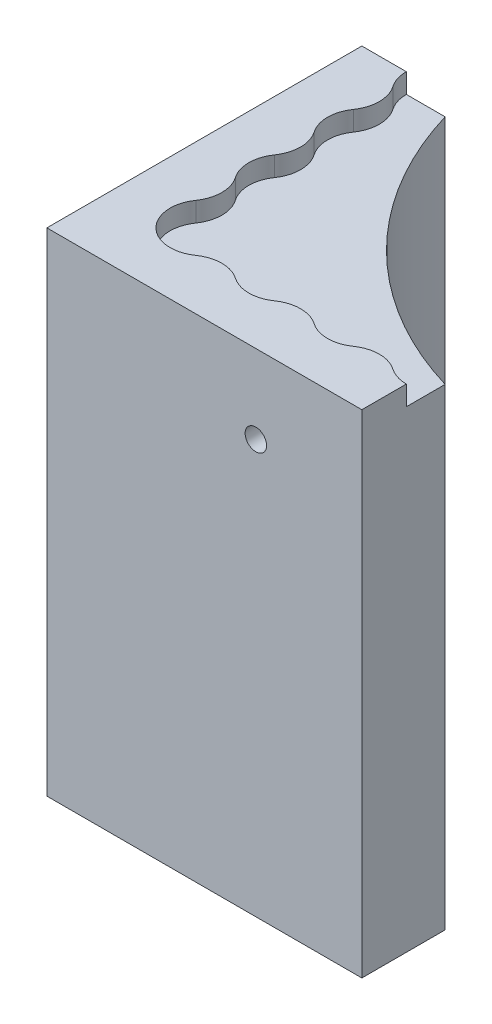
SolidWorks part; units mm, degrees
material "PET"
ref_plane "Front" through (0, 0, 0) normal (0, 0, 1) x (1, 0, 0)
ref_plane "Top" through (0, 0, 0) normal (0, 1, 0) x (1, 0, 0)
ref_plane "Right" through (0, 0, 0) normal (1, 0, 0) x (0, 0, -1)
sketch "Sketch1" plane through (0, 0, 0) normal (0, 1, 0) x (1, 0, 0)
  line L1 (0, 0) -> (50.8, 0)
  line L2 (0, 0) -> (0, 50.8)
  line L3 (0, 50.8) -> (50.8, 50.8)
  line L4 (50.8, 0) -> (50.8, 50.8)
  circle A0 centre (66.675, 66.675) radius 55.5625 construction
  dimension "D1" = 66.675
  dimension "D2" = 111.125
  dimension "D3" = 66.675
  dimension "D4" = 50.8
extrude "Boss-Extrude1" add sketch "Sketch1" along normal blind 79.375
sketch "Sketch2" plane through (0, 79.375, 0) normal (0, 1, 0) x (1, 0, 0)
  line L8 (129.2582, 124.9484) -> (133.499, 78.5045) construction
  line L9 (85.192, 137.4546) -> (125.4736, 129.1805) construction
  line L10 (129.2582, 124.9484) -> (133.499, 78.5045) construction
  line L11 (85.192, 137.4546) -> (125.4736, 129.1805) construction
  line L12 (130.017, 125.0177) -> (134.2578, 78.5738)
  line L13 (85.3453, 138.201) -> (125.6269, 129.9269)
  arc A0 (8.7916, 91.6214) -> (8.7916, 98.8786) centre (3.5805, 95.25) ccw construction
  arc A1 (8.7916, 91.6214) -> (8.7916, 86.1786) centre (12.7, 88.9) ccw construction
  arc A2 (8.7916, 78.9214) -> (8.7916, 86.1786) centre (3.5805, 82.55) ccw construction
  arc A3 (8.7916, 78.9214) -> (8.7796, 73.4959) centre (12.7, 76.2) ccw construction
  arc A4 (8.8014, 66.3169) -> (8.7796, 73.4959) centre (3.5524, 69.8905) ccw construction
  arc A5 (8.8014, 66.3169) -> (8.8053, 60.7032) centre (12.9199, 63.5129) ccw construction
  arc A6 (8.7834, 53.5096) -> (8.8053, 60.7032) centre (3.5613, 57.1223) ccw construction
  arc A7 (8.7834, 53.5096) -> (8.7916, 48.0786) centre (12.7, 50.8) ccw construction
  arc A8 (8.7916, 40.8214) -> (8.7916, 48.0786) centre (3.5805, 44.45) ccw construction
  arc A9 (8.7916, 40.8214) -> (8.7916, 35.3786) centre (12.7, 38.1) ccw construction
  arc A10 (8.7916, 28.1214) -> (8.7916, 35.3786) centre (3.5805, 31.75) ccw construction
  arc A11 (8.7916, 28.1214) -> (8.7916, 22.6786) centre (12.7, 25.4) ccw construction
  arc A12 (8.7916, 15.4214) -> (8.7916, 22.6786) centre (3.5805, 19.05) ccw construction
  arc A13 (8.7916, 15.4214) -> (15.4214, 8.7916) centre (12.7, 12.7) ccw construction
  arc A14 (22.6786, 8.7916) -> (15.4214, 8.7916) centre (19.05, 3.5805) ccw construction
  arc A15 (22.6786, 8.7916) -> (28.1214, 8.7916) centre (25.4, 12.7) ccw construction
  arc A16 (35.3786, 8.7916) -> (28.1214, 8.7916) centre (31.75, 3.5805) ccw construction
  arc A17 (35.3786, 8.7916) -> (40.8214, 8.7916) centre (38.1, 12.7) ccw construction
  arc A18 (48.0786, 8.7916) -> (40.8214, 8.7916) centre (44.45, 3.5805) ccw construction
  arc A19 (48.0786, 8.7916) -> (53.5096, 8.7834) centre (50.8, 12.7) ccw construction
  arc A20 (60.7032, 8.8053) -> (53.5096, 8.7834) centre (57.1223, 3.5613) ccw construction
  arc A21 (60.7032, 8.8053) -> (66.3169, 8.8014) centre (63.5129, 12.9199) ccw construction
  arc A22 (73.4959, 8.7796) -> (66.3169, 8.8014) centre (69.8905, 3.5524) ccw construction
  arc A23 (73.4959, 8.7796) -> (78.9214, 8.7916) centre (76.2, 12.7) ccw construction
  arc A24 (86.1786, 8.7916) -> (78.9214, 8.7916) centre (82.55, 3.5805) ccw construction
  arc A25 (86.1786, 8.7916) -> (91.6214, 8.7916) centre (88.9, 12.7) ccw construction
  arc A26 (98.8786, 8.7916) -> (91.6214, 8.7916) centre (95.25, 3.5805) ccw construction
  arc A27 (98.8786, 8.7916) -> (105.5642, 15.3394) centre (101.6, 12.7) ccw construction
  arc A28 (113.5841, 27.9306) -> (105.5642, 15.3394) centre (112.3572, 19.8624) ccw construction
  arc A29 (113.5841, 27.9306) -> (119.0625, 32.6538) centre (114.3, 32.639) ccw construction
  arc A30 (119.9168, 35.8549) -> (119.0625, 32.6538) centre (125.4124, 32.6736) ccw construction
  arc A31 (119.9168, 35.8549) -> (127.8227, 59.9277) centre (66.675, 66.675) ccw construction
  arc A32 (132.1466, 72.652) -> (127.8227, 59.9277) centre (158.75, 56.515) ccw construction
  arc A33 (132.1466, 72.652) -> (133.499, 78.5045) centre (123.9376, 77.6314) ccw construction
  arc A34 (129.2582, 124.9484) -> (125.4736, 129.1805) centre (124.5154, 124.5154) ccw construction
  arc A35 (85.192, 137.4546) -> (76.9535, 135.2891) centre (83.2602, 128.0498) ccw construction
  arc A36 (59.9277, 127.8227) -> (76.9535, 135.2891) centre (56.515, 158.75) ccw construction
  arc A37 (59.9277, 127.8227) -> (35.8549, 119.9168) centre (66.675, 66.675) ccw construction
  arc A38 (32.6538, 119.0625) -> (35.8549, 119.9168) centre (32.6736, 125.4124) ccw construction
  arc A39 (32.6538, 119.0625) -> (27.9306, 113.5841) centre (32.639, 114.3) ccw construction
  arc A40 (15.3394, 105.5642) -> (27.9306, 113.5841) centre (19.8624, 112.3572) ccw construction
  arc A41 (15.3394, 105.5642) -> (8.7916, 98.8786) centre (12.7, 101.6) ccw construction
  arc A42 (8.7916, 91.6214) -> (8.7916, 98.8786) centre (3.5805, 95.25) ccw construction
  arc A43 (8.7916, 91.6214) -> (8.7916, 86.1786) centre (12.7, 88.9) ccw construction
  arc A44 (8.7916, 78.9214) -> (8.7916, 86.1786) centre (3.5805, 82.55) ccw construction
  arc A45 (8.7916, 78.9214) -> (8.7796, 73.4959) centre (12.7, 76.2) ccw construction
  arc A46 (8.8014, 66.3169) -> (8.7796, 73.4959) centre (3.5524, 69.8905) ccw construction
  arc A47 (8.8014, 66.3169) -> (8.8053, 60.7032) centre (12.9199, 63.5129) ccw construction
  arc A48 (8.7834, 53.5096) -> (8.8053, 60.7032) centre (3.5613, 57.1223) ccw construction
  arc A49 (8.7834, 53.5096) -> (8.7916, 48.0786) centre (12.7, 50.8) ccw construction
  arc A50 (8.7916, 40.8214) -> (8.7916, 48.0786) centre (3.5805, 44.45) ccw construction
  arc A51 (8.7916, 40.8214) -> (8.7916, 35.3786) centre (12.7, 38.1) ccw construction
  arc A52 (8.7916, 28.1214) -> (8.7916, 35.3786) centre (3.5805, 31.75) ccw construction
  arc A53 (8.7916, 28.1214) -> (8.7916, 22.6786) centre (12.7, 25.4) ccw construction
  arc A54 (8.7916, 15.4214) -> (8.7916, 22.6786) centre (3.5805, 19.05) ccw construction
  arc A55 (8.7916, 15.4214) -> (15.4214, 8.7916) centre (12.7, 12.7) ccw construction
  arc A56 (22.6786, 8.7916) -> (15.4214, 8.7916) centre (19.05, 3.5805) ccw construction
  arc A57 (22.6786, 8.7916) -> (28.1214, 8.7916) centre (25.4, 12.7) ccw construction
  arc A58 (35.3786, 8.7916) -> (28.1214, 8.7916) centre (31.75, 3.5805) ccw construction
  arc A59 (35.3786, 8.7916) -> (40.8214, 8.7916) centre (38.1, 12.7) ccw construction
  arc A60 (48.0786, 8.7916) -> (40.8214, 8.7916) centre (44.45, 3.5805) ccw construction
  arc A61 (48.0786, 8.7916) -> (53.5096, 8.7834) centre (50.8, 12.7) ccw construction
  arc A62 (60.7032, 8.8053) -> (53.5096, 8.7834) centre (57.1223, 3.5613) ccw construction
  arc A63 (60.7032, 8.8053) -> (66.3169, 8.8014) centre (63.5129, 12.9199) ccw construction
  arc A64 (73.4959, 8.7796) -> (66.3169, 8.8014) centre (69.8905, 3.5524) ccw construction
  arc A65 (73.4959, 8.7796) -> (78.9214, 8.7916) centre (76.2, 12.7) ccw construction
  arc A66 (86.1786, 8.7916) -> (78.9214, 8.7916) centre (82.55, 3.5805) ccw construction
  arc A67 (86.1786, 8.7916) -> (91.6214, 8.7916) centre (88.9, 12.7) ccw construction
  arc A68 (98.8786, 8.7916) -> (91.6214, 8.7916) centre (95.25, 3.5805) ccw construction
  arc A69 (98.8786, 8.7916) -> (105.5642, 15.3394) centre (101.6, 12.7) ccw construction
  arc A70 (113.5841, 27.9306) -> (105.5642, 15.3394) centre (112.3572, 19.8624) ccw construction
  arc A71 (113.5841, 27.9306) -> (119.0625, 32.6538) centre (114.3, 32.639) ccw construction
  arc A72 (119.9168, 35.8549) -> (119.0625, 32.6538) centre (125.4124, 32.6736) ccw construction
  arc A73 (119.9168, 35.8549) -> (127.8227, 59.9277) centre (66.675, 66.675) ccw construction
  arc A74 (132.1466, 72.652) -> (127.8227, 59.9277) centre (158.75, 56.515) ccw construction
  arc A75 (132.1466, 72.652) -> (133.499, 78.5045) centre (123.9376, 77.6314) ccw construction
  arc A76 (129.2582, 124.9484) -> (125.4736, 129.1805) centre (124.5154, 124.5154) ccw construction
  arc A77 (85.192, 137.4546) -> (76.9535, 135.2891) centre (83.2602, 128.0498) ccw construction
  arc A78 (59.9277, 127.8227) -> (76.9535, 135.2891) centre (56.515, 158.75) ccw construction
  arc A79 (59.9277, 127.8227) -> (35.8549, 119.9168) centre (66.675, 66.675) ccw construction
  arc A80 (32.6538, 119.0625) -> (35.8549, 119.9168) centre (32.6736, 125.4124) ccw construction
  arc A81 (32.6538, 119.0625) -> (27.9306, 113.5841) centre (32.639, 114.3) ccw construction
  arc A82 (15.3394, 105.5642) -> (27.9306, 113.5841) centre (19.8624, 112.3572) ccw construction
  arc A83 (15.3394, 105.5642) -> (8.7916, 98.8786) centre (12.7, 101.6) ccw construction
  arc A84 (132.7981, 72.2568) -> (134.2578, 78.5738) centre (123.9376, 77.6314) ccw
  arc A85 (132.7981, 72.2568) -> (128.5801, 59.8441) centre (158.75, 56.515) ccw
  arc A86 (120.5763, 35.4731) -> (128.5801, 59.8441) centre (66.675, 66.675) ccw
  arc A87 (120.5763, 35.4731) -> (119.8245, 32.6562) centre (125.4124, 32.6736) ccw
  arc A88 (113.4695, 27.1773) -> (119.8245, 32.6562) centre (114.3, 32.639) ccw
  arc A89 (113.4695, 27.1773) -> (106.1985, 15.7617) centre (112.3572, 19.8624) ccw
  arc A90 (98.4431, 8.1663) -> (106.1985, 15.7617) centre (101.6, 12.7) ccw
  arc A91 (98.4431, 8.1663) -> (92.0569, 8.1663) centre (95.25, 3.5805) ccw
  arc A92 (85.7431, 8.1663) -> (92.0569, 8.1663) centre (88.9, 12.7) ccw
  arc A93 (85.7431, 8.1663) -> (79.3569, 8.1663) centre (82.55, 3.5805) ccw
  arc A94 (73.0633, 8.1523) -> (79.3569, 8.1663) centre (76.2, 12.7) ccw
  arc A95 (73.0633, 8.1523) -> (66.7457, 8.1715) centre (69.8905, 3.5524) ccw
  arc A96 (60.2735, 8.176) -> (66.7457, 8.1715) centre (63.5129, 12.9199) ccw
  arc A97 (60.2735, 8.176) -> (53.9431, 8.1568) centre (57.1223, 3.5613) ccw
  arc A98 (47.6431, 8.1663) -> (53.9431, 8.1568) centre (50.8, 12.7) ccw
  arc A99 (47.6431, 8.1663) -> (41.2569, 8.1663) centre (44.45, 3.5805) ccw
  arc A100 (34.9431, 8.1663) -> (41.2569, 8.1663) centre (38.1, 12.7) ccw
  arc A101 (34.9431, 8.1663) -> (28.5569, 8.1663) centre (31.75, 3.5805) ccw
  arc A102 (22.2431, 8.1663) -> (28.5569, 8.1663) centre (25.4, 12.7) ccw
  arc A103 (22.2431, 8.1663) -> (15.8569, 8.1663) centre (19.05, 3.5805) ccw
  arc A104 (8.1663, 15.8569) -> (15.8569, 8.1663) centre (12.7, 12.7) ccw
  arc A105 (8.1663, 15.8569) -> (8.1663, 22.2431) centre (3.5805, 19.05) ccw
  arc A106 (8.1663, 28.5569) -> (8.1663, 22.2431) centre (12.7, 25.4) ccw
  arc A107 (8.1663, 28.5569) -> (8.1663, 34.9431) centre (3.5805, 31.75) ccw
  arc A108 (8.1663, 41.2569) -> (8.1663, 34.9431) centre (12.7, 38.1) ccw
  arc A109 (8.1663, 41.2569) -> (8.1663, 47.6431) centre (3.5805, 44.45) ccw
  arc A110 (8.1568, 53.9431) -> (8.1663, 47.6431) centre (12.7, 50.8) ccw
  arc A111 (8.1568, 53.9431) -> (8.176, 60.2735) centre (3.5613, 57.1223) ccw
  arc A112 (8.1715, 66.7457) -> (8.176, 60.2735) centre (12.9199, 63.5129) ccw
  arc A113 (8.1715, 66.7457) -> (8.1523, 73.0633) centre (3.5524, 69.8905) ccw
  arc A114 (8.1663, 79.3569) -> (8.1523, 73.0633) centre (12.7, 76.2) ccw
  arc A115 (8.1663, 79.3569) -> (8.1663, 85.7431) centre (3.5805, 82.55) ccw
  arc A116 (8.1663, 92.0569) -> (8.1663, 85.7431) centre (12.7, 88.9) ccw
  arc A117 (8.1663, 92.0569) -> (8.1663, 98.4431) centre (3.5805, 95.25) ccw
  arc A118 (15.7617, 106.1985) -> (8.1663, 98.4431) centre (12.7, 101.6) ccw
  arc A119 (15.7617, 106.1985) -> (27.1773, 113.4695) centre (19.8624, 112.3572) ccw
  arc A120 (32.6562, 119.8245) -> (27.1773, 113.4695) centre (32.639, 114.3) ccw
  arc A121 (32.6562, 119.8245) -> (35.4731, 120.5763) centre (32.6736, 125.4124) ccw
  arc A122 (59.8441, 128.5801) -> (35.4731, 120.5763) centre (66.675, 66.675) ccw
  arc A123 (59.8441, 128.5801) -> (76.4529, 135.8637) centre (56.515, 158.75) ccw
  arc A124 (85.3453, 138.201) -> (76.4529, 135.8637) centre (83.2602, 128.0498) ccw
  arc A125 (130.017, 125.0177) -> (125.6269, 129.9269) centre (124.5154, 124.5154) ccw
  dimension "D1" = 0.762
extrude "Cut-Extrude1" cut sketch "Sketch2" against normal blind 3.175
sketch "Sketch3" plane through (0, 79.375, 0) normal (0, 1, 0) x (1, 0, 0)
  circle A0 centre (66.675, 66.675) radius 55.5625 construction
  circle A1 centre (66.675, 66.675) radius 55.5625
extrude "Cut-Extrude2" cut sketch "Sketch3" against normal through all
hole_wizard "#8-32 Tapped Hole1" positions "Sketch4" profile "Sketch5" tap size "#8-32" standard "ANSI Inch"
sketch "Sketch4" plane through (393.7, -15.875, 0) normal (0, 0, 1) x (1, 0, 0)
  point P0 (-300, 82.55)
  point P3 (-240, 82.55)
  point P6 (-180, 82.55)
  point P9 (-60, 82.55)
  point P12 (0, 82.55)
  point P15 (60, 82.55)
  point P18 (120, 82.55)
  point P21 (180, 82.55)
  point P24 (240, 82.55)
  point P27 (-120, 82.55)
  point P30 (-360, 82.55)
  point P33 (300, 82.55)
  point P36 (360, 82.55)
sketch "Sketch5" plane through (93.7, 66.675, 0) normal (1, 0, 0) x (0, -1, 0)
  line L0 (0, 0) -> (0, 11.7464)
  line L1 (0, 11.7464) -> (1.7272, 10.7086)
  line L2 (1.7272, 10.7086) -> (1.7272, 0)
  line L3 (1.7272, 0) -> (0, 0)
  line L4 (0, 11.7464) -> (-1.7272, 10.7086) construction
  line L5 (0, -6.35) -> (0, 107.95) construction
  dimension "Tap Drill Dia." = 3.4544
  dimension "Tap Drill Depth" = 10.7086
  dimension "Drill Angle" = 118
hole_wizard "#8-32 Tapped Hole2" positions "Sketch6" profile "Sketch7" tap size "#8-32" standard "ANSI Inch"
sketch "Sketch6" plane through (0, -15.875, -393.7) normal (-1, 0, 0) x (0, 0, 1)
  point P0 (-300, 82.55)
  point P3 (-240, 82.55)
  point P6 (-180, 82.55)
  point P9 (-60, 82.55)
  point P12 (0, 82.55)
  point P15 (60, 82.55)
  point P18 (120, 82.55)
  point P21 (180, 82.55)
  point P24 (240, 82.55)
  point P27 (-120, 82.55)
  point P30 (-360, 82.55)
  point P33 (300, 82.55)
  point P36 (360, 82.55)
sketch "Sketch7" plane through (0, 66.675, -693.7) normal (0, 1, 0) x (0, 0, 1)
  line L0 (0, 0) -> (0, 11.7464)
  line L1 (0, 11.7464) -> (1.7272, 10.7086)
  line L2 (1.7272, 10.7086) -> (1.7272, 0)
  line L3 (1.7272, 0) -> (0, 0)
  line L4 (0, 11.7464) -> (-1.7272, 10.7086) construction
  line L5 (0, -6.35) -> (0, 107.95) construction
  dimension "Tap Drill Dia." = 3.4544
  dimension "Tap Drill Depth" = 10.7086
  dimension "Drill Angle" = 118
